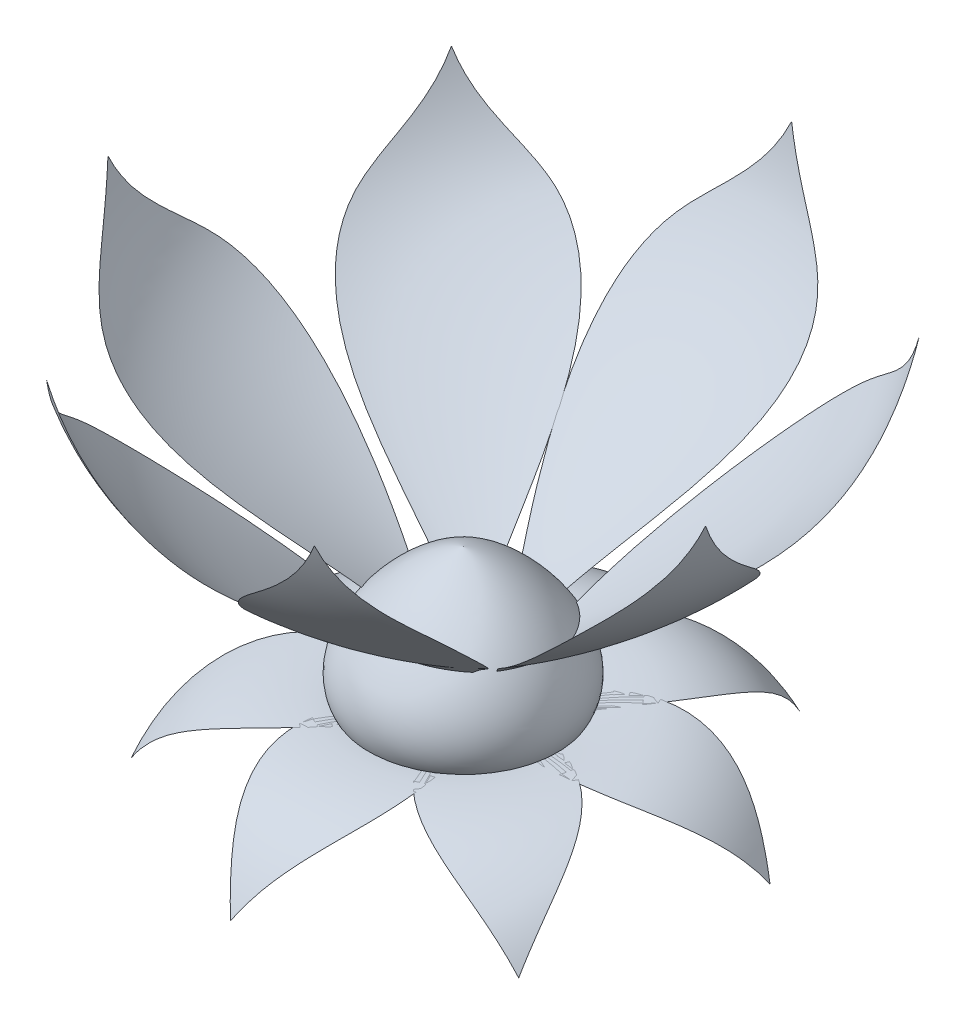
SolidWorks part; units mm, degrees
ref_plane "Front Plane" through (0, 0, 0) normal (0, 0, 1) x (1, 0, 0)
ref_plane "Top Plane" through (0, 0, 0) normal (0, 1, 0) x (1, 0, 0)
ref_plane "Right Plane" through (0, 0, 0) normal (1, 0, 0) x (0, 0, -1)
sketch "Sketch1" plane through (0, 0, 0) normal (1, 0, 0) x (0, 0, -1)
  line L0 (0, 0) -> (-1.9737, 26.6067) construction
  spline S0 degree 3 poles (0, 0) (-4.0618, 6.7075) (-22.6642, 9.3125) (-23.0216, 25.7849) (-25.0573, 31.5352) knots 0 0 0 0 0.564314 1 1 1 1
  point P2 (0, 0)
  point P6 (-2.0047, 32.4971)
  point P8 (-26.453, 33.4292)
  point P9 (-11.8673, 10.2261)
  point P11 (0, 0)
  point P12 (0, 0)
  point P13 (0, 0)
  point P14 (-19.3812, 15.733)
  point P15 (-1.9737, 26.6067)
  point P16 (-9.5564, 7.4273)
  point P17 (-19.2469, 14.0637)
surface "Surface-Revolve1" sketch "Sketch1" parameters "D1"=360
sketch "Sketch2" plane through (0, 0, 0) normal (1, 0, 0) x (0, 0, -1)
  line L0 (0, 0) -> (0, -6.441) construction
  spline S0 degree 2 poles (0, 0) (-13.0774, 5.4527) (-15.5434, -6.441) knots 0 0 0 1 1 1
  point P2 (0, 0)
surface "Surface-Revolve2" sketch "Sketch2" parameters "D1"=360
sketch "Sketch3" plane through (0, 0, 0) normal (0, 1, 0) x (1, 0, 0)
  line L0 (0, 0) -> (0, 24.3669) construction
  spline S0 degree 3 poles (0, 1.7552) (-2.1287, 5.5564) (-8.915, 14.8287) (-1.2244, 17.9344) (0, 18.6292) knots 0 0 0 0 0.752772 1 1 1 1
  spline S1 degree 3 poles (0, 1.7552) (2.1287, 5.5564) (8.915, 14.8287) (1.2244, 17.9344) (0, 18.6292) knots 0 0 0 0 0.752772 1 1 1 1
  point P5 (-3.4043, 11.9386)
  point P7 (-1.3381, 4.0182)
  point P9 (-3.6995, 11.4959)
  point P11 (0, 0)
  point P12 (-4.4374, 11.8402)
  point P13 (-4.1422, 16.0219)
  point P14 (-2.5716, 17.2498)
surface "Surface-Trim2"
sketch "Sketch4" plane through (0, 0, 0) normal (0, 1, 0) x (1, 0, 0)
  line L0 (0, 0) -> (0, -25.2866) construction
  spline S0 degree 2 poles (0, 0) (-6.9599, -7.7132) (0, -14.3852) knots 0 0 0 1 1 1
  spline S1 degree 2 poles (0, 0) (6.9599, -7.7132) (0, -14.3852) knots 0 0 0 1 1 1
surface "Surface-Trim3"
sketch "Sketch5" plane through (0, 0, 0) normal (1, 0, 0) x (0, 0, -1)
  line L0 (-0.6906, -0.7551) -> (-0.6906, 9.3628)
  spline S0 degree 3 poles (-0.6906, 9.3628) (3.5943, 8.2564) (9.9349, 0.1016) (-0.6906, -0.7551) knots 0 0 0 0 1 1 1 1
  point P3 (3.2398, 6.8165)
revolve "Revolve2" add sketch "Sketch5" angle 360 about L0
sketch "Sketch6" plane through (0, 0, 0) normal (1, 0, 0) x (0, 0, -1)
  line L0 (0, 0) -> (0, 15.3139) construction
pattern_circular "CirPattern1" count 7 over 312 about axis through (0, 0, 0) along (0, 1, 0) of bodies 104
pattern_circular "CirPattern3" count 8 over 359 about axis through (0, 0, 0) along (0, 1, 0) of bodies 105
sketch "Sketch7" plane through (0, 0, 0) normal (0, 1, 0) x (1, 0, 0)
  circle A0 centre (0, 0) radius 1.15
  dimension "D1" = 2.3
extrude "Boss-Extrude1" add sketch "Sketch7" against normal blind 2
